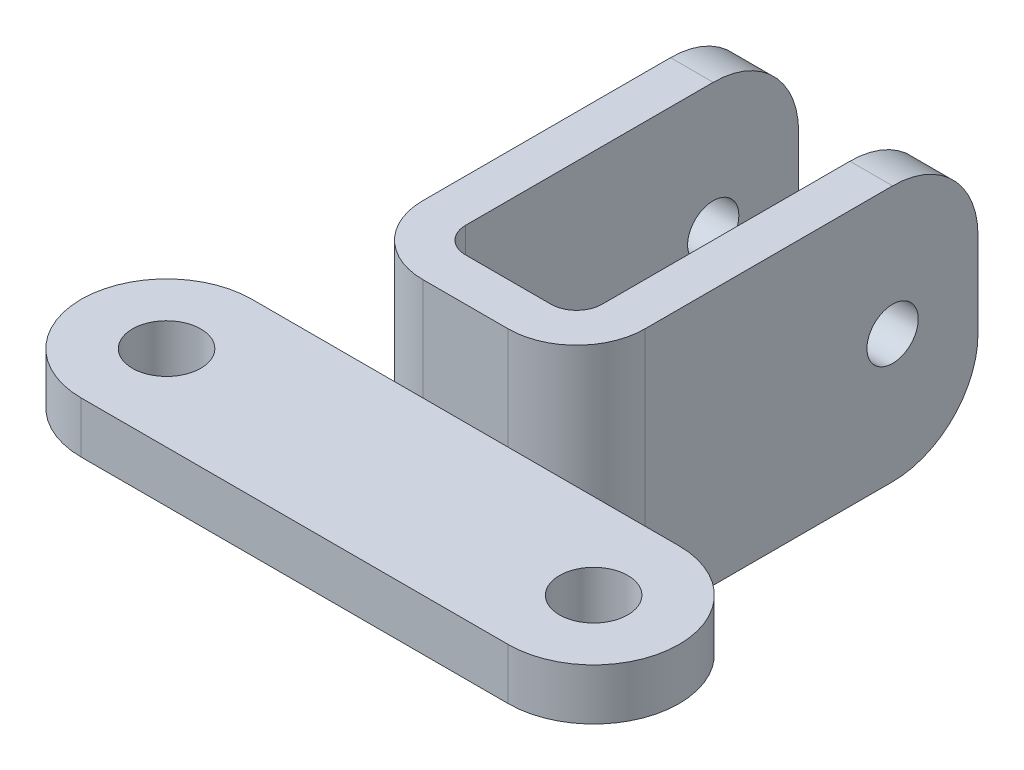
SolidWorks part; units mm, degrees
ref_plane "Front Plane" through (0, 0, 0) normal (0, 0, 1) x (1, 0, 0)
ref_plane "Top Plane" through (0, 0, 0) normal (0, 1, 0) x (1, 0, 0)
ref_plane "Right Plane" through (0, 0, 0) normal (1, 0, 0) x (0, 0, -1)
sketch "Sketch1" plane through (0, 0, 0) normal (0, 1, 0) x (1, 0, 0)
  line L0 (0, 55.2839) -> (0, -57.5582) construction
  line L1 (-13, 47) -> (-13, 8)
  line L2 (-5, 0) -> (0, 0)
  line L3 (0, 0) -> (5, 0)
  line L4 (13, 8) -> (13, 47)
  arc A0 (-13, 8) -> (-5, 0) centre (-5, 8) ccw
  arc A1 (5, 0) -> (13, 8) centre (5, 8) ccw
  point P11 (0, 0)
  point P13 (0, 0)
  point P14 (0, -10.0911)
  point P15 (0, 0)
  dimension "D1" = 8
  dimension "D2" = 8
  dimension "D3" = 26
  dimension "D4" = 47
  dimension "D5" = 47
extrude "Extrude-Thin1" add sketch "Sketch1" along normal mid plane 30 thin thin type one direction reverse wall 5
fillet "Fillet1" radius 10 4 edges at (10.5, 15, -47) (10.5, -15, -47) (-10.5, -15, -47) (-10.5, 15, -47)
sketch "Sketch2" plane through (0, 0, 0) normal (0, 1, 0) x (1, 0, 0)
  line L0 (-5, 0) -> (5, 0) construction
  line L1 (-5, 0) -> (5, 0)
  line L2 (-25, 0) -> (25, 0)
  line L3 (25, -20) -> (-25, -20)
  line L4 (0, 0) -> (0, 49.7994) construction
  line L10 (13, 8) -> (13, 37)
  line L11 (13, 37) -> (8, 37)
  line L12 (8, 37) -> (8, 8)
  line L13 (5, 5) -> (-5, 5)
  line L14 (-8, 8) -> (-8, 37)
  line L15 (-8, 37) -> (-13, 37)
  line L16 (-13, 37) -> (-13, 8)
  line L17 (-5, 0) -> (5, 0)
  line L18 (13, 8) -> (13, 37)
  line L19 (13, 37) -> (8, 37)
  line L20 (8, 37) -> (8, 8)
  line L21 (5, 5) -> (-5, 5)
  line L22 (-8, 8) -> (-8, 37)
  line L23 (-8, 37) -> (-13, 37)
  line L24 (-13, 37) -> (-13, 8)
  line L25 (-5, 0) -> (5, 0)
  arc A0 (25, 0) -> (25, -20) centre (25, -10) cw
  arc A1 (-25, -20) -> (-25, 0) centre (-25, -10) cw
  circle A2 centre (-25, -10) radius 4
  circle A3 centre (25, -10) radius 4
  arc A4 (5, 5) -> (8, 8) centre (5, 8) ccw
  arc A5 (-8, 8) -> (-5, 5) centre (-5, 8) ccw
  arc A6 (-13, 8) -> (-5, 0) centre (-5, 8) ccw
  arc A7 (5, 0) -> (13, 8) centre (5, 8) ccw
  arc A8 (5, 5) -> (8, 8) centre (5, 8) ccw
  arc A9 (-8, 8) -> (-5, 5) centre (-5, 8) ccw
  arc A10 (-13, 8) -> (-5, 0) centre (-5, 8) ccw
  arc A11 (5, 0) -> (13, 8) centre (5, 8) ccw
  dimension "D2" = 50
  dimension "D3" = 10
  dimension "D4" = 8
  dimension "D5" = 8
  dimension "D1" = 0
extrude "Boss-Extrude1" add sketch "Sketch2" along normal mid plane 6 contours A1 L3 A0 L2 L25 L1 A3 A2
sketch "Sketch3" plane through (13, 0, 0) normal (1, 0, 0) x (0, 0, -1)
  line L0 (0, 0) -> (73.8853, 0) construction
  line L4 (47, -5) -> (47, 5)
  line L5 (37, 15) -> (8, 15)
  line L6 (8, 15) -> (8, -15)
  line L7 (8, -15) -> (37, -15)
  line L8 (47, -5) -> (47, 5)
  line L9 (37, 15) -> (8, 15)
  line L10 (8, 15) -> (8, -15)
  line L11 (8, -15) -> (37, -15)
  circle A0 centre (37, 0) radius 3
  arc A2 (47, 5) -> (37, 15) centre (37, 5) ccw
  arc A3 (37, -15) -> (47, -5) centre (37, -5) ccw
  arc A4 (47, 5) -> (37, 15) centre (37, 5) ccw
  arc A5 (37, -15) -> (47, -5) centre (37, -5) ccw
  dimension "D2" = 6
  dimension "D3" = 10
  dimension "D1" = 0
extrude "Cut-Extrude1" cut sketch "Sketch3" against normal through all both and the other way through all contours A0 L0 | L0 A0
